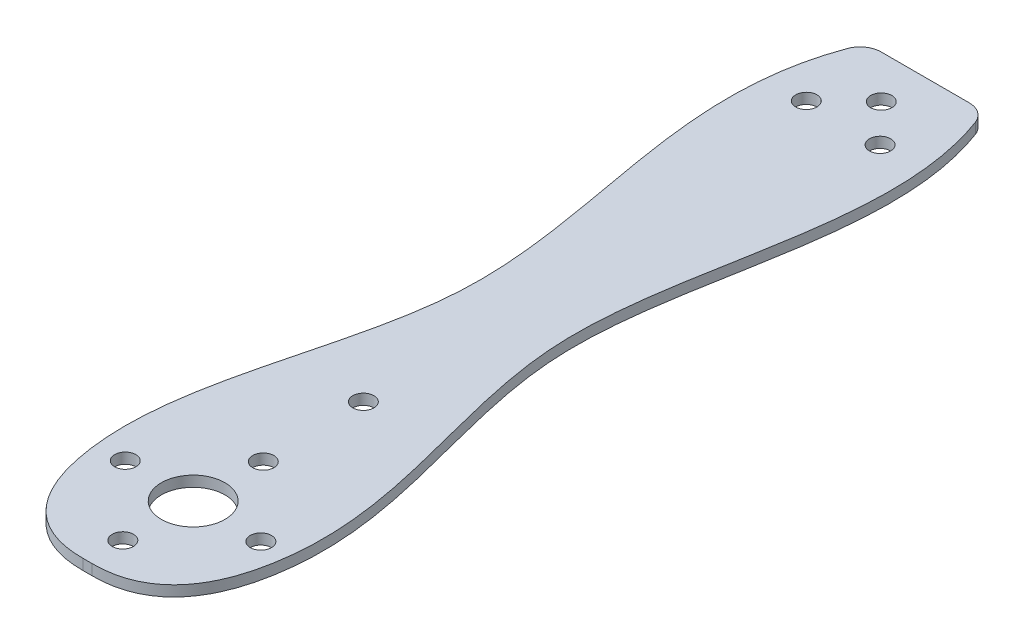
SolidWorks part; units mm, degrees
ref_plane "Front Plane" through (0, 0, 0) normal (0, 0, 1) x (1, 0, 0)
ref_plane "Top Plane" through (0, 0, 0) normal (0, 1, 0) x (1, 0, 0)
ref_plane "Right Plane" through (0, 0, 0) normal (1, 0, 0) x (0, 0, -1)
sketch "Sketch1" plane through (0, 0, 0) normal (0, 1, 0) x (1, 0, 0)
  line L2 (5.2752, 88.9) -> (-5.2747, 88.9)
  arc A0 (-0.5524, -11.4436) -> (0.5462, -11.4451) centre (-0.1058, -87.6423) cw
  arc A1 (7.6564, 87.2441) -> (5.2752, 88.9) centre (5.2752, 86.36) ccw
  arc A2 (-5.2747, 88.9) -> (-7.6561, 87.2435) centre (-5.2747, 86.36) ccw
  spline S0 degree 3 poles (-0.5524, -11.4436) (-4.8921, -11.469) (-9.5294, -8.0668) (-14.6459, 10.818) (0.653, 38.8317) (-11.939, 68.4666) (-8.6939, 84.4462) (-7.6561, 87.2435) knots 0.003862 0.003862 0.003862 0.003862 0.096354 0.162149 0.527592 0.902665 0.983926 0.983926 0.983926 0.983926
  spline S1 degree 3 poles (0.5462, -11.4451) (4.7056, -11.4807) (9.4269, -8.1856) (14.7819, 10.7254) (-0.6874, 38.8281) (11.9385, 68.4664) (8.695, 84.4468) (7.6564, 87.2441) knots 0.003868 0.003868 0.003868 0.003868 0.093614 0.162314 0.527685 0.902684 0.983934 0.983934 0.983934 0.983934
  dimension "D1" = 2.54
  dimension "D2" = 76.2
extrude "Boss-Extrude2" add sketch "Sketch1" along normal blind 1.27
sketch "Sketch2" plane through (0, 1.27, 0) normal (0, 1, 0) x (1, 0, 0)
  circle A0 centre (0, 21.59) radius 1.27
extrude "Cut-Extrude1" cut sketch "Sketch2" against normal through all
sketch3d "3DSketch1"
  circle A0 centre (0.2113, 3.81, -9.3896) radius 1.27 construction
  circle A1 centre (-8.1504, 3.81, -1.2161) radius 1.27 construction
  circle A2 centre (0.1037, 3.81, -1.0967) radius 3.81 construction
  circle A3 centre (8.3574, 3.81, -0.9527) radius 1.27 construction
  circle A4 centre (-0.0286, 3.81, 7.1959) radius 1.27 construction
  circle A5 centre (0.2113, 3.81, -9.3896) radius 1.27
  circle A6 centre (-8.1504, 3.81, -1.2161) radius 1.27
  circle A7 centre (0.1037, 3.81, -1.0967) radius 3.81
  circle A8 centre (8.3574, 3.81, -0.9527) radius 1.27
  circle A9 centre (-0.0286, 3.81, 7.1959) radius 1.27
  point P2 (0.2113, 5.08, -9.3896)
  point P5 (-8.1504, 5.08, -1.2161)
  point P8 (0.1037, 7.62, -1.0967)
  point P11 (8.3574, 5.08, -0.9527)
  point P14 (-0.0286, 5.08, 7.1959)
  point P16 (0.2113, 5.08, -9.3896)
  point P18 (-8.1504, 5.08, -1.2161)
  point P20 (0.1037, 7.62, -1.0967)
  point P22 (8.3574, 5.08, -0.9527)
  point P24 (-0.0286, 5.08, 7.1959)
extrude "Cut-Extrude8" cut sketch "3DSketch1" along direction (0, 1, 0) on the side against the normal through all
sketch "Sketch4" plane through (0, 1.27, 0) normal (0, 1, 0) x (1, 0, 0)
  circle A0 centre (-4.6847, 79.3365) radius 1.27 construction
  circle A1 centre (-0.1235, 83.7544) radius 1.27 construction
  circle A2 centre (4.2944, 79.1933) radius 1.27 construction
  circle A3 centre (-4.6847, 79.3365) radius 1.27
  circle A4 centre (-0.1235, 83.7544) radius 1.27
  circle A5 centre (4.2944, 79.1933) radius 1.27
extrude "Cut-Extrude9" cut sketch "Sketch4" against normal through all
